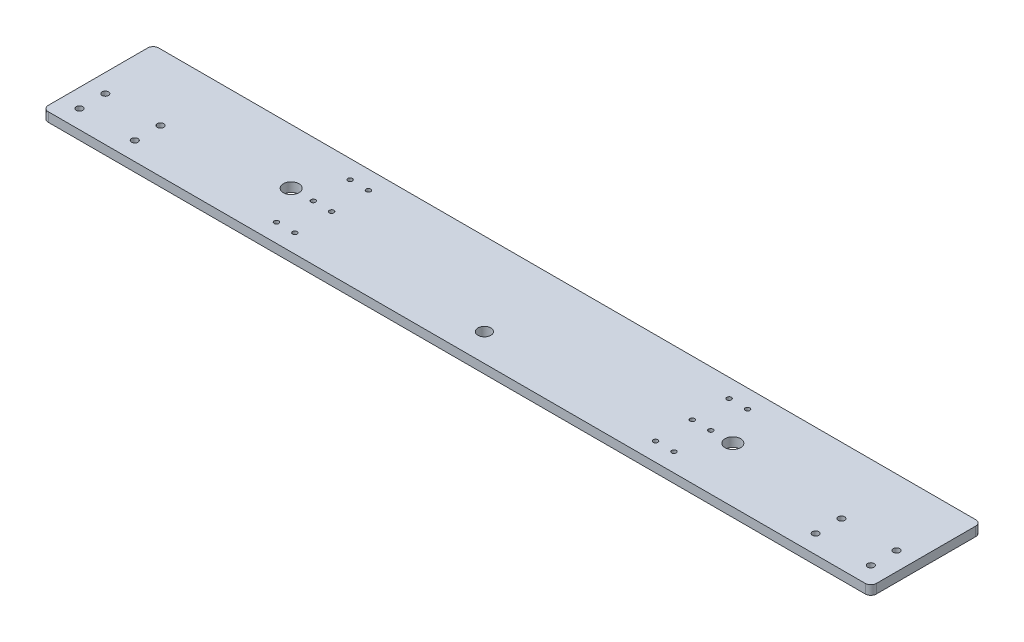
SolidWorks part; units mm, degrees
ref_plane "Front" through (0, 0, 0) normal (0, 0, 1) x (1, 0, 0)
ref_plane "Top" through (0, 0, 0) normal (0, 1, 0) x (1, 0, 0)
ref_plane "Right" through (0, 0, 0) normal (1, 0, 0) x (0, 0, -1)
sketch "草图1" plane through (0, 0, 0) normal (0, 1, 0) x (1, 0, 0)
  line L1 (-225, -30) -> (225, -30)
  line L2 (-225, -30) -> (-225, 30)
  line L3 (-225, 30) -> (225, 30)
  line L4 (225, -30) -> (225, 30)
  line L5 (-225, -30) -> (225, 30) construction
  line L6 (-225, 30) -> (225, -30) construction
  point P0 (0, 0)
  dimension "D1" = 450
  dimension "D2" = 60
extrude "凸台-拉伸1" add sketch "草图1" against normal blind 5 contours L3 L4 L1 L2
sketch "草图2" plane through (0, 0, 0) normal (0, 1, 0) x (1, 0, 0)
  line L0 (-225, -30) -> (225, -30) construction
  circle A0 centre (0, -15) radius 3.5
  dimension "D1" = 7
  dimension "D2" = 15
extrude "切除-拉伸2" cut sketch "草图2" against normal through all contours A0
sketch "草图4" plane through (0, 0, 0) normal (0, 1, 0) x (1, 0, 0)
  line L0 (-225, -30) -> (225, -30) construction
  circle A0 centre (-98, -20) radius 1
  circle A1 centre (0, -15) radius 2.65 construction
  dimension "D1" = 98
  dimension "D2" = 10
  dimension "D3" = 2
extrude "切除-拉伸4" cut sketch "草图4" against normal through all contours A0
pattern_linear "阵列(线性)2" count 3 spacing 20 along (0, 0, -1) count 2 spacing 10 along (-1, 0, 0) of "切除-拉伸4"
mirror "镜向1" about plane through (0, 0, 0) normal (1, 0, 0) of "阵列(线性)2", "切除-拉伸4"
sketch "草图6" plane through (0, 0, 0) normal (0, 1, 0) x (1, 0, 0)
  line L0 (-225, 0) -> (-130.6748, 0) construction
  line L1 (-225, -30) -> (-225, 30) construction
  line L2 (-225, -30) -> (225, -30) construction
  circle A0 centre (-215, -20) radius 1.75
  dimension "D3" = 3.5
  dimension "D1" = 10
  dimension "D2" = 10
extrude "切除-拉伸5" cut sketch "草图6" against normal through all contours A0
pattern_linear "阵列(线性)3" count 2 spacing 14 along (0, 0, -1) count 2 spacing 30 along (1, 0, 0) of "切除-拉伸5"
mirror "镜向2" about plane through (0, 0, 0) normal (1, 0, 0) of "阵列(线性)3", "切除-拉伸5"
sketch "草图7" plane through (0, 0, 0) normal (0, 1, 0) x (1, 0, 0)
  circle A0 centre (-120, 0) radius 4.25
  dimension "D1" = 8.5
  dimension "D2" = 120
extrude "切除-拉伸6" cut sketch "草图7" against normal blind 10
mirror "镜向3" about plane through (0, 0, 0) normal (1, 0, 0) of "切除-拉伸6"
fillet "圆角3" radius 3 1 edges at (-225, -2.5, 30)
fillet "圆角4" radius 3 1 edges at (-225, -2.5, -30)
fillet "圆角5" radius 3 1 edges at (225, -2.5, -30)
fillet "圆角6" radius 3 1 edges at (225, -2.5, 30)
hole_wizard "M3 螺纹孔2" positions "草图10" profile "草图11" tap size "M3" standard "GB" end condition through all
sketch "草图10" plane through (0, 0, 0) normal (0, 1, 0) x (1, 0, 0)
  point P0 (-98, -20)
  point P3 (-98, 0)
  point P6 (-98, 20)
  point P9 (-108, 20)
  point P12 (-108, 0)
  point P15 (-108, -20)
  point P18 (98, -20)
  point P21 (108, -20)
  point P24 (98, 0)
  point P27 (108, 0)
  point P30 (108, 20)
  point P33 (98, 20)
sketch "草图11" plane through (-98, 0, 20) normal (1, 0, 0) x (0, 0, 1)
  line L0 (0, 0) -> (0, 5)
  line L1 (0, 5) -> (1.25, 5)
  line L2 (1.25, 5) -> (1.25, 0)
  line L5 (1.25, 0) -> (0, 0)
  line L11 (0, -6.35) -> (0, 107.95) construction
  dimension "通孔螺纹孔钻头直径" = 2.5
  dimension "通孔螺纹孔钻头深度" = 5
cosmetic thread "孔螺蚊线1" parameters "D2"=3
cosmetic thread "孔螺蚊线2" parameters "D2"=3
cosmetic thread "孔螺蚊线3" parameters "D2"=3
cosmetic thread "孔螺蚊线4" parameters "D2"=3
cosmetic thread "孔螺蚊线5" parameters "D2"=3
cosmetic thread "孔螺蚊线6" parameters "D2"=3
cosmetic thread "孔螺蚊线7" parameters "D2"=3
cosmetic thread "孔螺蚊线8" parameters "D2"=3
cosmetic thread "孔螺蚊线9" parameters "D2"=3
cosmetic thread "孔螺蚊线10" parameters "D2"=3
cosmetic thread "孔螺蚊线11" parameters "D2"=3
cosmetic thread "孔螺蚊线12" parameters "D2"=3
